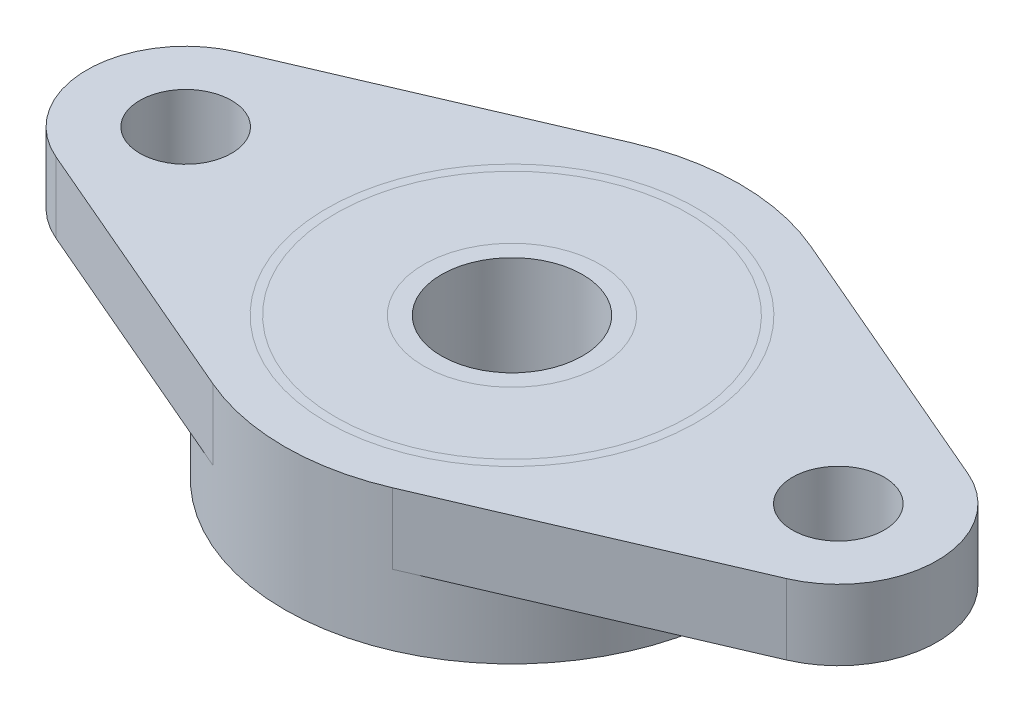
SolidWorks part; units mm, degrees
material "6061 合金"
ref_plane "前视基准面" through (0, 0, 0) normal (0, 0, 1) x (1, 0, 0)
ref_plane "上视基准面" through (0, 0, 0) normal (0, 1, 0) x (1, 0, 0)
ref_plane "右视基准面" through (0, 0, 0) normal (1, 0, 0) x (0, 0, -1)
sketch "草图1" plane through (0, 0, 0) normal (0, 1, 0) x (1, 0, 0)
  line L0 (-18.5, 0) -> (18.5, 0) construction
  line L1 (0, -15.8438) -> (0, 17.0598) construction
  line L2 (-20.7097, -5.1456) -> (-5.0903, -11.8532)
  line L3 (20.7097, -5.1456) -> (5.0903, -11.8532)
  line L4 (20.7097, 5.1456) -> (5.0903, 11.8532)
  line L5 (-20.7097, 5.1456) -> (-5.0903, 11.8532)
  arc A0 (-5.0903, -11.8532) -> (5.0903, -11.8532) centre (0, 0) ccw
  circle A1 centre (-18.5, 0) radius 2.6
  arc A2 (-20.7097, 5.1456) -> (-20.7097, -5.1456) centre (-18.5, 0) ccw
  arc A3 (20.7097, 5.1456) -> (20.7097, -5.1456) centre (18.5, 0) cw
  circle A4 centre (18.5, 0) radius 2.6
  arc A5 (5.0903, 11.8532) -> (-5.0903, 11.8532) centre (0, 0) ccw
  circle A6 centre (0, 0) radius 4
  dimension "D1" = 25.8
  dimension "D3" = 5.2
  dimension "D4" = 11.2
  dimension "D5" = 8
  dimension "D2" = 37
extrude "凸台-拉伸1" add sketch "草图1" along normal blind 4
sketch "草图2" plane through (0, 0, 0) normal (0, -1, 0) x (1, 0, 0)
  circle A0 centre (0, 0) radius 12.9
  circle A1 centre (0, 0) radius 4
  dimension "D1" = 25.8
  dimension "D2" = 8
extrude "凸台-拉伸2" add sketch "草图2" along normal blind 4
sketch "草图3" plane through (0, -4, 0) normal (0, -1, 0) x (1, 0, 0)
  circle A0 centre (0, 0) radius 6.1
  circle A1 centre (0, 0) radius 4 construction
  circle A2 centre (0, 0) radius 4
  dimension "D1" = 12.2
extrude "凸台-拉伸3" add sketch "草图3" along normal blind 3.5
sketch "草图4" plane through (0, 4, 0) normal (0, 1, 0) x (1, 0, 0)
  circle A0 centre (0, 0) radius 10
  circle A1 centre (0, 0) radius 5
  circle A2 centre (0, 0) radius 10.5
  dimension "D1" = 20
  dimension "D2" = 10
  dimension "D3" = 21
split line "分割线1"
sketch "草图5" plane through (0, -4, 0) normal (0, -1, 0) x (1, 0, 0)
  circle A0 centre (0, 0) radius 10.5
  circle A1 centre (0, 0) radius 10
  dimension "D1" = 21
  dimension "D2" = 20
split line "分割线2"
sketch "草图6" plane through (0, 0, 0) normal (0, 0, 1) x (1, 0, 0)
  line L0 (0, -4) -> (0, -7.5) construction
  line L1 (-6.1, -4) -> (6.1, -4) construction
  line L2 (-6.1, -7.5) -> (6.1, -7.5) construction
  circle A0 centre (0, -5.75) radius 1
  dimension "D1" = 2
extrude "切除-拉伸1" cut sketch "草图6" against normal blind 10
cosmetic thread "装饰螺纹线2" parameters "D1"=2.227, "D2"=6
sketch "草图7" plane through (0, 0, 0) normal (1, 0, 0) x (0, 0, -1)
  line L0 (0, -4) -> (0, -7.5) construction
  line L1 (-6.1, -4) -> (6.1, -4) construction
  line L2 (-6.1, -7.5) -> (6.1, -7.5) construction
  circle A0 centre (0, -5.75) radius 1
  dimension "D1" = 2
extrude "切除-拉伸2" cut sketch "草图7" against normal blind 10
cosmetic thread "装饰螺纹线1" parameters "D2"=6
